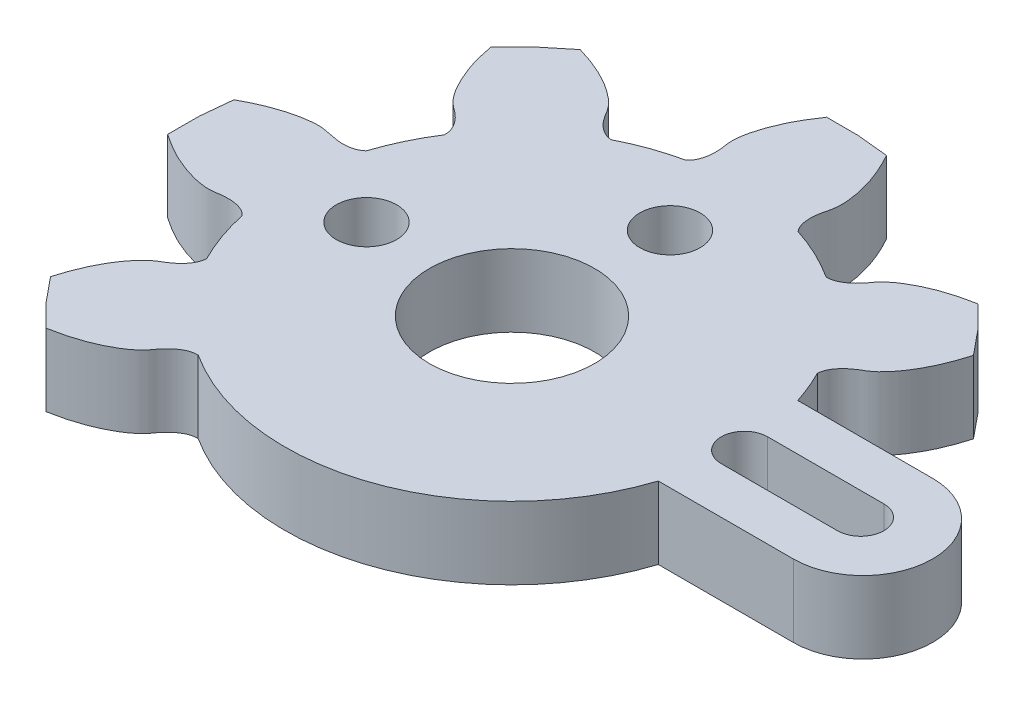
SolidWorks part; units mm, degrees
ref_plane "Front Plane" through (0, 0, 0) normal (0, 0, 1) x (1, 0, 0)
ref_plane "Top Plane" through (0, 0, 0) normal (0, 1, 0) x (1, 0, 0)
ref_plane "Right Plane" through (0, 0, 0) normal (1, 0, 0) x (0, 0, -1)
sketch "Sketch1" plane through (0, 0, 0) normal (0, 1, 0) x (1, 0, 0)
  line L0 (3.621, -0.0001) -> (-10.658, -0.0001) construction
  line L1 (-3.508, 0.8974) -> (3.508, -0.8973) construction
  line L2 (0.8972, 3.508) -> (-0.8972, -3.5081) construction
  line L3 (-6.7582, 1.6977) -> (-6.7583, -0.9523) construction
  line L4 (-8.0831, 0.3728) -> (-5.4334, 0.3728) construction
  line L5 (-1.1163, 6.723) -> (1.5333, 6.723) construction
  line L6 (0.2086, 8.0479) -> (0.2084, 5.3979) construction
  line L8 (10.2001, 1.02) -> (15.3001, 1.02)
  line L10 (10.2001, -1.02) -> (15.3001, -1.02)
  line L11 (15.402, 3.06) -> (15.402, -3.06) construction
  line L12 (15.402, -3.06) -> (9.479, -3.06)
  line L13 (15.402, 3.06) -> (9.4793, 3.06)
  line L809 (11.6208, 8.6285) -> (10.7416, 9.701)
  line L810 (10.7416, 9.701) -> (9.7639, 10.6846)
  line L853 (2.1159, 14.3182) -> (0.7358, 14.455)
  line L854 (0.7358, 14.455) -> (-0.651, 14.4591)
  line L875 (-2.1014, 9.7366) -> (-2.1021, 9.7364)
  line L897 (-8.6285, 11.6207) -> (-9.701, 10.7414)
  line L898 (-9.701, 10.7414) -> (-10.6845, 9.7637)
  line L919 (-8.3708, 5.3989) -> (-8.3715, 5.3976)
  line L920 (-9.4728, 3.0795) -> (-9.4729, 3.079)
  line L941 (-14.3183, 2.1157) -> (-14.4551, 0.7356)
  line L942 (-14.4551, 0.7356) -> (-14.459, -0.6512)
  line L963 (-9.7366, -2.1014) -> (-9.7363, -2.1023)
  line L964 (-8.8759, -4.5205) -> (-8.8757, -4.5211)
  line L985 (-11.6206, -8.6286) -> (-10.7416, -9.7011)
  line L986 (-10.7416, -9.7011) -> (-9.7637, -10.6846)
  circle A0 centre (0, 0) radius 3.621
  circle A1 centre (-6.7583, 0.3727) radius 1.3249
  circle A2 centre (0.2085, 6.723) radius 1.3248
  arc A3 (8.8758, 4.5212) -> (9.4793, 3.06) centre (0, 0) cw
  arc A4 (15.3001, -1.02) -> (15.3001, 1.02) centre (15.3001, -0.0001) ccw
  arc A5 (10.2001, 1.02) -> (10.2001, -1.02) centre (10.2001, -0.0001) ccw
  arc A6 (3.0705, 9.4841) -> (5.4131, 8.371) centre (0, 0) cw
  arc A7 (15.402, -3.06) -> (15.402, 3.06) centre (15.402, 0) ccw
  arc A8 (-8.3715, 5.3976) -> (-9.4728, 3.0795) centre (0, 0) ccw
  arc A9 (-2.1021, 9.7364) -> (-4.5212, 8.8755) centre (0, 0) ccw
  arc A11 (-9.7363, -2.1023) -> (-8.8759, -4.5205) centre (0, 0) ccw
  arc A12 (-5.3979, -8.3713) -> (9.479, -3.06) centre (0, 0) ccw
  spline S0 degree 3 poles (8.8758, 4.5212) (8.88, 4.5545) (8.8843, 4.5879) (8.8886, 4.6212) (8.8894, 4.6279) (8.8912, 4.6414) (8.8949, 4.6615) (8.8986, 4.6746) (8.9005, 4.6811) (8.9056, 4.6988) (8.9106, 4.7166) (8.9157, 4.7343) (8.9173, 4.7399) (8.9205, 4.7511) (8.9261, 4.7677) (8.9305, 4.7784) (8.9327, 4.7838) (8.939, 4.7991) (8.9452, 4.8145) (8.9515, 4.8298) (8.9535, 4.8347) (8.9575, 4.8445) (8.9641, 4.8591) (8.969, 4.8685) (8.9714, 4.8732) (8.9785, 4.8869) (8.9855, 4.9005) (8.9926, 4.9142) (8.9949, 4.9186) (8.9995, 4.9275) (9.0068, 4.9406) (9.012, 4.9492) (9.0147, 4.9534) (9.0223, 4.9659) (9.03, 4.9785) (9.0377, 4.991) (9.0414, 4.997) (9.0488, 5.0091) (9.0615, 5.0262) (9.07, 5.0376) (9.0742, 5.0433) (9.0909, 5.0656) (9.1077, 5.088) (9.1244, 5.1103) (9.1298, 5.1176) (9.1407, 5.1322) (9.1582, 5.1533) (9.1705, 5.1668) (9.1767, 5.1735) (9.1948, 5.1932) (9.2129, 5.213) (9.2311, 5.2327) (9.237, 5.2392) (9.249, 5.2522) (9.2677, 5.271) (9.2807, 5.2829) (9.2872, 5.2889) (9.3065, 5.3066) (9.3257, 5.3243) (9.345, 5.342) (9.3545, 5.3507) (9.3735, 5.3682) (9.4047, 5.3914) (9.4254, 5.4068) (9.4357, 5.4145) (9.4769, 5.4451) (9.5181, 5.4758) (9.5593, 5.5064) (9.5729, 5.5166) (9.6003, 5.5369) (9.643, 5.5651) (9.6725, 5.5822) (9.6872, 5.5907) (9.7313, 5.6163) (9.7755, 5.6419) (9.8196, 5.6675) (9.8343, 5.676) (9.8638, 5.6931) (9.9064, 5.7216) (9.9336, 5.7422) (9.9472, 5.7525) (9.9881, 5.7835) (10.029, 5.8146) (10.07, 5.8457) (10.0838, 5.8561) (10.1114, 5.8771) (10.1504, 5.9118) (10.1746, 5.9367) (10.1867, 5.9491) (10.2236, 5.987) (10.2605, 6.0248) (10.2974, 6.0627) (10.3098, 6.0755) (10.3347, 6.1011) (10.3704, 6.1411) (10.3929, 6.1688) (10.4042, 6.1826) (10.4385, 6.2246) (10.4727, 6.2667) (10.507, 6.3087) (10.5186, 6.3229) (10.5417, 6.3512) (10.5749, 6.3951) (10.5959, 6.4251) (10.6064, 6.4401) (10.6384, 6.4856) (10.6703, 6.5311) (10.7023, 6.5767) (10.7131, 6.592) (10.7346, 6.6227) (10.7655, 6.6699) (10.785, 6.7019) (10.7948, 6.7179) (10.8245, 6.7665) (10.8541, 6.8152) (10.8838, 6.8638) (10.8938, 6.8802) (10.9139, 6.913) (10.9424, 6.9631) (10.9606, 6.997) (10.9696, 7.0139) (10.9972, 7.0653) (11.0247, 7.1168) (11.0523, 7.1682) (11.0615, 7.1855) (11.0801, 7.2202) (11.1065, 7.273) (11.1232, 7.3087) (11.1315, 7.3265) (11.1568, 7.3806) (11.1822, 7.4347) (11.2075, 7.4888) (11.216, 7.507) (11.2331, 7.5435) (11.2573, 7.5989) (11.2725, 7.6361) (11.2802, 7.6547) (11.3033, 7.7113) (11.3264, 7.7678) (11.3496, 7.8244) (11.3573, 7.8434) (11.3729, 7.8815) (11.3949, 7.9392) (11.4086, 7.978) (11.4155, 7.9974) (11.4363, 8.0563) (11.4572, 8.1151) (11.478, 8.174) (11.485, 8.1938) (11.4991, 8.2335) (11.5187, 8.2935) (11.531, 8.3337) (11.5371, 8.3538) (11.565, 8.4454) (11.5929, 8.537) (11.6208, 8.6285) knots 0 0 0 0 0.019853 0.019853 0.019853 0.023862 0.02787 0.031878 0.031878 0.031878 0.042761 0.042761 0.042761 0.046198 0.049635 0.053072 0.053072 0.053072 0.06284 0.06284 0.06284 0.065977 0.069113 0.07225 0.07225 0.07225 0.081322 0.081322 0.081322 0.084276 0.08723 0.090185 0.090185 0.090185 0.098852 0.098852 0.098852 0.103039 0.107226 0.111413 0.111413 0.111413 0.127893 0.127893 0.127893 0.133271 0.13865 0.144028 0.144028 0.144028 0.15986 0.15986 0.15986 0.16507 0.170279 0.175489 0.175489 0.175489 0.190945 0.190945 0.190945 0.198563 0.206181 0.213799 0.213799 0.213799 0.244106 0.244106 0.244106 0.254159 0.264213 0.274266 0.274266 0.274266 0.304379 0.304379 0.304379 0.314436 0.324492 0.334549 0.334549 0.334549 0.364891 0.364891 0.364891 0.375124 0.385357 0.39559 0.39559 0.39559 0.426817 0.426817 0.426817 0.437349 0.447881 0.458413 0.458413 0.458413 0.490441 0.490441 0.490441 0.501247 0.512053 0.522859 0.522859 0.522859 0.555709 0.555709 0.555709 0.566786 0.577862 0.588938 0.588938 0.588938 0.622581 0.622581 0.622581 0.633925 0.645269 0.656613 0.656613 0.656613 0.69106 0.69106 0.69106 0.702675 0.71429 0.725906 0.725906 0.725906 0.761174 0.761174 0.761174 0.77306 0.784946 0.796832 0.796832 0.796832 0.8329 0.8329 0.8329 0.845051 0.857203 0.869354 0.869354 0.869354 0.906216 0.906216 0.906216 0.918637 0.931058 0.943478 0.943478 0.943478 1 1 1 1
  spline S1 degree 3 poles (9.7639, 10.6846) (9.6699, 10.6662) (9.576, 10.6478) (9.4821, 10.6294) (9.4614, 10.6253) (9.4202, 10.6172) (9.3585, 10.6037) (9.3176, 10.5938) (9.2972, 10.5888) (9.2365, 10.574) (9.1759, 10.5592) (9.1152, 10.5444) (9.0952, 10.5396) (9.0552, 10.5298) (8.9956, 10.5138) (8.9561, 10.5022) (8.9363, 10.4964) (8.8777, 10.4791) (8.8192, 10.4619) (8.7606, 10.4446) (8.7412, 10.4389) (8.7026, 10.4276) (8.6451, 10.4091) (8.6071, 10.3958) (8.5881, 10.3892) (8.5317, 10.3695) (8.4754, 10.3498) (8.419, 10.3301) (8.4004, 10.3236) (8.3633, 10.3106) (8.3081, 10.2897) (8.2717, 10.2748) (8.2535, 10.2673) (8.1995, 10.2451) (8.1455, 10.223) (8.0915, 10.2008) (8.0738, 10.1935) (8.0382, 10.1789) (7.9855, 10.1555) (7.9508, 10.1389) (7.9335, 10.1306) (7.8821, 10.106) (7.8307, 10.0814) (7.7793, 10.0568) (7.7624, 10.0487) (7.7286, 10.0325) (7.6786, 10.0066) (7.6458, 9.9883) (7.6295, 9.9791) (7.5809, 9.952) (7.5324, 9.9248) (7.4839, 9.8977) (7.4679, 9.8887) (7.4359, 9.8709) (7.3889, 9.8424) (7.3584, 9.8223) (7.3431, 9.8122) (7.2978, 9.7824) (7.2524, 9.7525) (7.2071, 9.7227) (7.1922, 9.7129) (7.1624, 9.6933) (7.1189, 9.6619) (7.091, 9.6397) (7.077, 9.6286) (7.0356, 9.5957) (6.9941, 9.5629) (6.9527, 9.53) (6.9391, 9.5192) (6.912, 9.4976) (6.8734, 9.4623) (6.8497, 9.437) (6.8379, 9.4243) (6.8028, 9.3868) (6.7677, 9.3492) (6.7326, 9.3117) (6.721, 9.2992) (6.6977, 9.2743) (6.6651, 9.2348) (6.6451, 9.2072) (6.6351, 9.1934) (6.6052, 9.1521) (6.5753, 9.1107) (6.5454, 9.0694) (6.5354, 9.0556) (6.5155, 9.028) (6.483, 8.9883) (6.46, 8.9632) (6.4485, 8.9507) (6.4139, 8.9128) (6.3792, 8.875) (6.3445, 8.8371) (6.3358, 8.8276) (6.3184, 8.8086) (6.2921, 8.78) (6.2728, 8.7628) (6.2632, 8.7543) (6.2436, 8.7369) (6.2241, 8.7195) (6.2045, 8.7021) (6.1979, 8.6963) (6.1847, 8.6846) (6.1641, 8.6678) (6.15, 8.6573) (6.1429, 8.652) (6.1215, 8.636) (6.1, 8.6199) (6.0785, 8.6039) (6.0713, 8.5985) (6.0567, 8.5876) (6.0339, 8.5724) (6.0183, 8.563) (6.0104, 8.5583) (5.9865, 8.5439) (5.9626, 8.5296) (5.9386, 8.5152) (5.9326, 8.5116) (5.9204, 8.5043) (5.9021, 8.4933) (5.8893, 8.4872) (5.8829, 8.4841) (5.8697, 8.4778) (5.8565, 8.4714) (5.8433, 8.4651) (5.8388, 8.4629) (5.8297, 8.4586) (5.8159, 8.4526) (5.8066, 8.4489) (5.8019, 8.4471) (5.7876, 8.4414) (5.7733, 8.4358) (5.7589, 8.4301) (5.754, 8.4282) (5.7441, 8.4243) (5.729, 8.4192) (5.7188, 8.4162) (5.7137, 8.4147) (5.6978, 8.41) (5.682, 8.4054) (5.6661, 8.4007) (5.6605, 8.3991) (5.6494, 8.3958) (5.6323, 8.392) (5.6209, 8.3899) (5.6151, 8.3889) (5.597, 8.3857) (5.5788, 8.3824) (5.5607, 8.3792) (5.554, 8.378) (5.5406, 8.3756) (5.5202, 8.374) (5.5066, 8.3736) (5.4998, 8.3734) (5.4709, 8.3726) (5.442, 8.3718) (5.4131, 8.371) knots 0 0 0 0 0.056516 0.056516 0.056516 0.068936 0.081355 0.093775 0.093775 0.093775 0.130635 0.130635 0.130635 0.142786 0.154938 0.167089 0.167089 0.167089 0.203158 0.203158 0.203158 0.215042 0.226926 0.23881 0.23881 0.23881 0.274066 0.274066 0.274066 0.285681 0.297296 0.308911 0.308911 0.308911 0.343368 0.343368 0.343368 0.354713 0.366059 0.377404 0.377404 0.377404 0.411046 0.411046 0.411046 0.42212 0.433194 0.444268 0.444268 0.444268 0.477104 0.477104 0.477104 0.487909 0.498714 0.509519 0.509519 0.509519 0.541555 0.541555 0.541555 0.552089 0.562624 0.573158 0.573158 0.573158 0.604391 0.604391 0.604391 0.614627 0.624863 0.635098 0.635098 0.635098 0.665448 0.665448 0.665448 0.675506 0.685563 0.695621 0.695621 0.695621 0.725735 0.725735 0.725735 0.735788 0.745841 0.755895 0.755895 0.755895 0.786201 0.786201 0.786201 0.793819 0.801436 0.809054 0.809054 0.809054 0.824508 0.824508 0.824508 0.829716 0.834924 0.840132 0.840132 0.840132 0.855952 0.855952 0.855952 0.861329 0.866706 0.872083 0.872083 0.872083 0.888565 0.888565 0.888565 0.892751 0.896937 0.901123 0.901123 0.901123 0.909781 0.909781 0.909781 0.912738 0.915695 0.918652 0.918652 0.918652 0.927749 0.927749 0.927749 0.930888 0.934027 0.937165 0.937165 0.937165 0.946918 0.946918 0.946918 0.950353 0.953788 0.957222 0.957222 0.957222 0.968108 0.968108 0.968108 0.972118 0.976128 0.980138 0.980138 0.980138 0.997214 0.997214 0.997214 0.997214
  spline S2 degree 3 poles (3.0705, 9.4841) (3.0528, 9.507) (3.0352, 9.5299) (3.0176, 9.5528) (3.0134, 9.5582) (3.0051, 9.569) (2.9935, 9.5858) (2.9869, 9.5977) (2.9836, 9.6036) (2.9747, 9.6197) (2.9657, 9.6358) (2.9568, 9.6519) (2.9539, 9.657) (2.9483, 9.6671) (2.9405, 9.6828) (2.936, 9.6935) (2.9338, 9.6989) (2.9274, 9.7141) (2.921, 9.7294) (2.9146, 9.7446) (2.9125, 9.7495) (2.9084, 9.7593) (2.9028, 9.7743) (2.8995, 9.7844) (2.8979, 9.7894) (2.8932, 9.8041) (2.8886, 9.8188) (2.8839, 9.8335) (2.8824, 9.8382) (2.8793, 9.8478) (2.8752, 9.8622) (2.8729, 9.872) (2.8717, 9.8768) (2.8683, 9.8911) (2.8649, 9.9054) (2.8615, 9.9197) (2.8598, 9.9265) (2.8565, 9.9403) (2.8534, 9.9615) (2.8513, 9.9755) (2.8503, 9.9825) (2.8463, 10.0102) (2.8423, 10.0378) (2.8383, 10.0655) (2.837, 10.0745) (2.8343, 10.0925) (2.8317, 10.1198) (2.831, 10.138) (2.8306, 10.1471) (2.8295, 10.1738) (2.8284, 10.2006) (2.8273, 10.2273) (2.8269, 10.2361) (2.8262, 10.2538) (2.8262, 10.2802) (2.8269, 10.2979) (2.8273, 10.3067) (2.8284, 10.3328) (2.8294, 10.359) (2.8305, 10.3851) (2.8311, 10.398) (2.8321, 10.4238) (2.8377, 10.4622) (2.8415, 10.4878) (2.8434, 10.5005) (2.8508, 10.5513) (2.8583, 10.6022) (2.8658, 10.6529) (2.8682, 10.6698) (2.8732, 10.7035) (2.8835, 10.7537) (2.8922, 10.7866) (2.8966, 10.8031) (2.9097, 10.8524) (2.9229, 10.9017) (2.936, 10.951) (2.9404, 10.9675) (2.9491, 11.0004) (2.9592, 11.0507) (2.9638, 11.0844) (2.9661, 11.1013) (2.9731, 11.1522) (2.98, 11.2032) (2.987, 11.2541) (2.9893, 11.2712) (2.994, 11.3056) (2.9971, 11.3578) (2.9966, 11.3924) (2.9964, 11.4098) (2.9957, 11.4626) (2.9951, 11.5155) (2.9944, 11.5684) (2.9941, 11.5862) (2.9937, 11.6219) (2.9905, 11.6754) (2.9869, 11.7109) (2.9851, 11.7286) (2.9796, 11.7826) (2.9741, 11.8365) (2.9686, 11.8905) (2.9667, 11.9087) (2.963, 11.9451) (2.9554, 11.9996) (2.9491, 12.0356) (2.946, 12.0536) (2.9364, 12.1084) (2.9268, 12.1632) (2.9172, 12.218) (2.9139, 12.2365) (2.9074, 12.2734) (2.8959, 12.3285) (2.8871, 12.365) (2.8827, 12.3833) (2.8693, 12.4387) (2.856, 12.4941) (2.8426, 12.5495) (2.8381, 12.5681) (2.8291, 12.6055) (2.8139, 12.6612) (2.8027, 12.6979) (2.7972, 12.7163) (2.7802, 12.7722) (2.7633, 12.828) (2.7464, 12.8839) (2.7406, 12.9027) (2.7292, 12.9404) (2.7105, 12.9964) (2.6971, 13.0334) (2.6905, 13.0519) (2.6701, 13.108) (2.6498, 13.1642) (2.6295, 13.2203) (2.6226, 13.2392) (2.6089, 13.2771) (2.5869, 13.3334) (2.5713, 13.3705) (2.5635, 13.389) (2.5399, 13.4453) (2.5162, 13.5017) (2.4926, 13.558) (2.4846, 13.5769) (2.4687, 13.6149) (2.4434, 13.6712) (2.4257, 13.7084) (2.4169, 13.727) (2.39, 13.7833) (2.3632, 13.8397) (2.3363, 13.896) (2.3273, 13.915) (2.3092, 13.953) (2.2807, 14.0093) (2.2609, 14.0464) (2.251, 14.065) (2.206, 14.1494) (2.1609, 14.2338) (2.1159, 14.3182) knots 0.00277 0.00277 0.00277 0.00277 0.019842 0.019842 0.019842 0.023849 0.027855 0.031862 0.031862 0.031862 0.042739 0.042739 0.042739 0.046172 0.049606 0.05304 0.05304 0.05304 0.062797 0.062797 0.062797 0.065935 0.069073 0.072212 0.072212 0.072212 0.081303 0.081303 0.081303 0.08426 0.087217 0.090174 0.090174 0.090174 0.098836 0.098836 0.098836 0.103026 0.107215 0.111405 0.111405 0.111405 0.127903 0.127903 0.127903 0.133281 0.138658 0.144036 0.144036 0.144036 0.159845 0.159845 0.159845 0.165051 0.170257 0.175463 0.175463 0.175463 0.190918 0.190918 0.190918 0.198537 0.206157 0.213776 0.213776 0.213776 0.244096 0.244096 0.244096 0.254153 0.26421 0.274268 0.274268 0.274268 0.304392 0.304392 0.304392 0.314451 0.32451 0.334568 0.334568 0.334568 0.364914 0.364914 0.364914 0.375147 0.385379 0.395612 0.395612 0.395612 0.426832 0.426832 0.426832 0.437363 0.447895 0.458426 0.458426 0.458426 0.490458 0.490458 0.490458 0.501264 0.512069 0.522874 0.522874 0.522874 0.555716 0.555716 0.555716 0.566793 0.577869 0.588946 0.588946 0.588946 0.622598 0.622598 0.622598 0.633945 0.645293 0.65664 0.65664 0.65664 0.691102 0.691102 0.691102 0.702718 0.714335 0.725952 0.725952 0.725952 0.761215 0.761215 0.761215 0.773099 0.784983 0.796867 0.796867 0.796867 0.832931 0.832931 0.832931 0.845081 0.857231 0.869382 0.869382 0.869382 0.90624 0.90624 0.90624 0.918658 0.931076 0.943495 0.943495 0.943495 1 1 1 1
  spline S3 degree 3 poles (-0.651, 14.4591) (-0.7044, 14.3797) (-0.7578, 14.3003) (-0.8112, 14.2209) (-0.823, 14.2034) (-0.8465, 14.1685) (-0.8805, 14.1153) (-0.9024, 14.0794) (-0.9133, 14.0614) (-0.9458, 14.0081) (-0.9782, 13.9547) (-1.0107, 13.9014) (-1.0214, 13.8838) (-1.0428, 13.8486) (-1.0736, 13.7951) (-1.0933, 13.759) (-1.1032, 13.7409) (-1.1324, 13.6873) (-1.1617, 13.6336) (-1.1909, 13.58) (-1.2005, 13.5623) (-1.2198, 13.527) (-1.2474, 13.4733) (-1.2649, 13.437) (-1.2736, 13.4189) (-1.2995, 13.3651) (-1.3255, 13.3113) (-1.3514, 13.2575) (-1.3599, 13.2398) (-1.377, 13.2044) (-1.4012, 13.1505) (-1.4164, 13.1142) (-1.424, 13.0961) (-1.4465, 13.0422) (-1.469, 12.9884) (-1.4915, 12.9345) (-1.4989, 12.9168) (-1.5137, 12.8813) (-1.5345, 12.8275) (-1.5473, 12.7913) (-1.5537, 12.7731) (-1.5726, 12.7194) (-1.5916, 12.6657) (-1.6105, 12.6119) (-1.6168, 12.5943) (-1.6292, 12.5589) (-1.6463, 12.5052) (-1.6565, 12.4691) (-1.6616, 12.451) (-1.6767, 12.3975) (-1.6918, 12.344) (-1.7069, 12.2905) (-1.7119, 12.2728) (-1.7218, 12.2376) (-1.7349, 12.1842) (-1.7423, 12.1484) (-1.7459, 12.1304) (-1.7569, 12.0773) (-1.7678, 12.0241) (-1.7787, 11.971) (-1.7823, 11.9535) (-1.7895, 11.9186) (-1.7981, 11.8657) (-1.8022, 11.8302) (-1.8042, 11.8125) (-1.8103, 11.76) (-1.8164, 11.7075) (-1.8224, 11.655) (-1.8244, 11.6378) (-1.8284, 11.6034) (-1.8307, 11.5511) (-1.8295, 11.5165) (-1.8289, 11.4992) (-1.8271, 11.4478) (-1.8254, 11.3964) (-1.8236, 11.345) (-1.823, 11.328) (-1.8218, 11.294) (-1.817, 11.2429) (-1.8116, 11.2092) (-1.8089, 11.1924) (-1.8009, 11.1421) (-1.7928, 11.0917) (-1.7848, 11.0414) (-1.7821, 11.0246) (-1.7768, 10.9909) (-1.7716, 10.9399) (-1.7701, 10.9059) (-1.7693, 10.8889) (-1.767, 10.8376) (-1.7648, 10.7863) (-1.7625, 10.735) (-1.7619, 10.7221) (-1.7608, 10.6963) (-1.7591, 10.6575) (-1.7606, 10.6318) (-1.7614, 10.6189) (-1.7629, 10.5928) (-1.7645, 10.5666) (-1.766, 10.5405) (-1.7665, 10.5317) (-1.7676, 10.5141) (-1.7703, 10.4878) (-1.7729, 10.4703) (-1.7741, 10.4616) (-1.778, 10.4351) (-1.7818, 10.4085) (-1.7857, 10.382) (-1.787, 10.373) (-1.7896, 10.355) (-1.795, 10.3281) (-1.7994, 10.3104) (-1.8016, 10.3016) (-1.8083, 10.2745) (-1.8151, 10.2474) (-1.8218, 10.2203) (-1.8235, 10.2134) (-1.827, 10.1997) (-1.8322, 10.179) (-1.8369, 10.1656) (-1.8392, 10.1589) (-1.8441, 10.1451) (-1.849, 10.1312) (-1.8538, 10.1174) (-1.8555, 10.1127) (-1.8588, 10.1032) (-1.8644, 10.0892) (-1.8684, 10.0801) (-1.8704, 10.0755) (-1.8765, 10.0614) (-1.8827, 10.0472) (-1.8888, 10.0331) (-1.8909, 10.0282) (-1.8952, 10.0185) (-1.9023, 10.0042) (-1.9074, 9.9948) (-1.9099, 9.9902) (-1.9179, 9.9757) (-1.9258, 9.9611) (-1.9337, 9.9466) (-1.9365, 9.9415) (-1.9421, 9.9313) (-1.9515, 9.9165) (-1.9581, 9.907) (-1.9614, 9.9022) (-1.9719, 9.8871) (-1.9825, 9.8719) (-1.993, 9.8568) (-1.9968, 9.8513) (-2.0046, 9.8401) (-2.0179, 9.8245) (-2.0272, 9.8147) (-2.0319, 9.8098) (-2.0551, 9.7854) (-2.0782, 9.761) (-2.1014, 9.7366) knots 0 0 0 0 0.056512 0.056512 0.056512 0.068933 0.081354 0.093775 0.093775 0.093775 0.130646 0.130646 0.130646 0.142799 0.154952 0.167105 0.167105 0.167105 0.203173 0.203173 0.203173 0.215055 0.226938 0.238821 0.238821 0.238821 0.274073 0.274073 0.274073 0.285688 0.297302 0.308917 0.308917 0.308917 0.343378 0.343378 0.343378 0.354724 0.36607 0.377416 0.377416 0.377416 0.411059 0.411059 0.411059 0.422134 0.433209 0.444285 0.444285 0.444285 0.477128 0.477128 0.477128 0.487935 0.498742 0.509549 0.509549 0.509549 0.541589 0.541589 0.541589 0.55212 0.562651 0.573182 0.573182 0.573182 0.604387 0.604387 0.604387 0.614619 0.624851 0.635083 0.635083 0.635083 0.665442 0.665442 0.665442 0.6755 0.685558 0.695616 0.695616 0.695616 0.725722 0.725722 0.725722 0.735777 0.745831 0.755886 0.755886 0.755886 0.786207 0.786207 0.786207 0.793826 0.801445 0.809064 0.809064 0.809064 0.824512 0.824512 0.824512 0.829719 0.834926 0.840133 0.840133 0.840133 0.855955 0.855955 0.855955 0.861333 0.866712 0.87209 0.87209 0.87209 0.888581 0.888581 0.888581 0.892768 0.896956 0.901143 0.901143 0.901143 0.909802 0.909802 0.909802 0.912758 0.915715 0.918672 0.918672 0.918672 0.927764 0.927764 0.927764 0.930904 0.934044 0.937184 0.937184 0.937184 0.946952 0.946952 0.946952 0.950388 0.953823 0.957258 0.957258 0.957258 0.968132 0.968132 0.968132 0.972138 0.976144 0.980151 0.980151 0.980151 1 1 1 1
  spline S4 degree 3 poles (-4.5212, 8.8755) (-4.5545, 8.8798) (-4.5878, 8.8841) (-4.6211, 8.8885) (-4.6279, 8.8893) (-4.6413, 8.8911) (-4.6615, 8.8948) (-4.6745, 8.8985) (-4.681, 8.9004) (-4.6988, 8.9054) (-4.7165, 8.9105) (-4.7342, 8.9155) (-4.7398, 8.9171) (-4.751, 8.9203) (-4.7676, 8.9259) (-4.7784, 8.9303) (-4.7838, 8.9325) (-4.7991, 8.9388) (-4.8144, 8.945) (-4.8297, 8.9513) (-4.8346, 8.9533) (-4.8445, 8.9573) (-4.859, 8.9639) (-4.8684, 8.9688) (-4.8731, 8.9712) (-4.8868, 8.9783) (-4.9005, 8.9854) (-4.9141, 8.9925) (-4.9186, 8.9947) (-4.9275, 8.9993) (-4.9406, 9.0067) (-4.9492, 9.0119) (-4.9534, 9.0145) (-4.9659, 9.0222) (-4.9785, 9.0298) (-4.991, 9.0375) (-4.997, 9.0412) (-5.0091, 9.0486) (-5.0263, 9.0613) (-5.0376, 9.0698) (-5.0433, 9.0741) (-5.0657, 9.0908) (-5.088, 9.1076) (-5.1104, 9.1243) (-5.1177, 9.1298) (-5.1323, 9.1407) (-5.1534, 9.1581) (-5.1668, 9.1705) (-5.1735, 9.1766) (-5.1932, 9.1947) (-5.213, 9.2129) (-5.2327, 9.231) (-5.2392, 9.2369) (-5.2521, 9.2489) (-5.2709, 9.2676) (-5.2829, 9.2805) (-5.2888, 9.287) (-5.3065, 9.3063) (-5.3243, 9.3255) (-5.342, 9.3448) (-5.3507, 9.3543) (-5.3682, 9.3733) (-5.3914, 9.4044) (-5.4068, 9.4251) (-5.4145, 9.4355) (-5.4451, 9.4767) (-5.4758, 9.5179) (-5.5064, 9.5591) (-5.5166, 9.5728) (-5.5369, 9.6001) (-5.5651, 9.6429) (-5.5822, 9.6724) (-5.5907, 9.6871) (-5.6163, 9.7312) (-5.6418, 9.7754) (-5.6674, 9.8195) (-5.6759, 9.8342) (-5.693, 9.8637) (-5.7215, 9.9064) (-5.7421, 9.9335) (-5.7524, 9.9471) (-5.7835, 9.988) (-5.8146, 10.029) (-5.8457, 10.0699) (-5.8562, 10.0837) (-5.8771, 10.1113) (-5.9119, 10.1504) (-5.9367, 10.1746) (-5.9491, 10.1867) (-5.987, 10.2236) (-6.0248, 10.2604) (-6.0627, 10.2973) (-6.0754, 10.3098) (-6.101, 10.3347) (-6.1411, 10.3703) (-6.1687, 10.3928) (-6.1825, 10.4041) (-6.2246, 10.4384) (-6.2666, 10.4726) (-6.3087, 10.5069) (-6.3229, 10.5185) (-6.3512, 10.5416) (-6.3951, 10.5747) (-6.4251, 10.5958) (-6.44, 10.6063) (-6.4856, 10.6382) (-6.5311, 10.6702) (-6.5766, 10.7021) (-6.592, 10.7129) (-6.6227, 10.7345) (-6.6699, 10.7653) (-6.7019, 10.7848) (-6.7179, 10.7946) (-6.7665, 10.8243) (-6.8152, 10.8541) (-6.8638, 10.8838) (-6.8802, 10.8938) (-6.913, 10.9138) (-6.9631, 10.9424) (-6.997, 10.9605) (-7.0139, 10.9696) (-7.0654, 10.9971) (-7.1169, 11.0246) (-7.1683, 11.0521) (-7.1857, 11.0614) (-7.2204, 11.0799) (-7.2732, 11.1063) (-7.3088, 11.123) (-7.3266, 11.1314) (-7.3807, 11.1567) (-7.4348, 11.1821) (-7.4888, 11.2074) (-7.5071, 11.216) (-7.5435, 11.2331) (-7.5989, 11.2573) (-7.6361, 11.2725) (-7.6547, 11.2801) (-7.7113, 11.3032) (-7.7678, 11.3263) (-7.8243, 11.3494) (-7.8434, 11.3572) (-7.8815, 11.3727) (-7.9392, 11.3947) (-7.978, 11.4085) (-7.9974, 11.4154) (-8.0562, 11.4362) (-8.1151, 11.4571) (-8.1739, 11.478) (-8.1937, 11.485) (-8.2334, 11.499) (-8.2934, 11.5187) (-8.3336, 11.531) (-8.3537, 11.5371) (-8.4453, 11.5649) (-8.5369, 11.5928) (-8.6285, 11.6207) knots 0 0 0 0 0.019841 0.019841 0.019841 0.023849 0.027857 0.031866 0.031866 0.031866 0.042756 0.042756 0.042756 0.046192 0.049628 0.053065 0.053065 0.053065 0.062824 0.062824 0.062824 0.065961 0.069099 0.072236 0.072236 0.072236 0.081321 0.081321 0.081321 0.084277 0.087233 0.090189 0.090189 0.090189 0.09885 0.09885 0.09885 0.10304 0.107229 0.111419 0.111419 0.111419 0.127918 0.127918 0.127918 0.133297 0.138675 0.144053 0.144053 0.144053 0.159864 0.159864 0.159864 0.165069 0.170274 0.175479 0.175479 0.175479 0.190927 0.190927 0.190927 0.198546 0.206165 0.213785 0.213785 0.213785 0.244108 0.244108 0.244108 0.254163 0.264219 0.274274 0.274274 0.274274 0.304382 0.304382 0.304382 0.314441 0.3245 0.334559 0.334559 0.334559 0.364922 0.364922 0.364922 0.375155 0.385388 0.395621 0.395621 0.395621 0.426826 0.426826 0.426826 0.437356 0.447886 0.458416 0.458416 0.458416 0.490452 0.490452 0.490452 0.501259 0.512065 0.522871 0.522871 0.522871 0.555716 0.555716 0.555716 0.566794 0.577871 0.588948 0.588948 0.588948 0.622602 0.622602 0.622602 0.633948 0.645295 0.656642 0.656642 0.656642 0.691098 0.691098 0.691098 0.702713 0.714328 0.725944 0.725944 0.725944 0.761203 0.761203 0.761203 0.773086 0.784969 0.796852 0.796852 0.796852 0.832913 0.832913 0.832913 0.845063 0.857213 0.869363 0.869363 0.869363 0.906223 0.906223 0.906223 0.918643 0.931062 0.943482 0.943482 0.943482 1 1 1 1
  spline S5 degree 3 poles (-10.6845, 9.7637) (-10.6661, 9.6698) (-10.6477, 9.5759) (-10.6293, 9.482) (-10.6253, 9.4613) (-10.6172, 9.42) (-10.6037, 9.3584) (-10.5938, 9.3175) (-10.5888, 9.2971) (-10.574, 9.2364) (-10.5593, 9.1757) (-10.5445, 9.1151) (-10.5396, 9.0951) (-10.5299, 9.0551) (-10.5139, 8.9954) (-10.5022, 8.9559) (-10.4964, 8.9362) (-10.4791, 8.8776) (-10.4619, 8.8191) (-10.4446, 8.7605) (-10.4389, 8.7412) (-10.4275, 8.7026) (-10.409, 8.6451) (-10.3958, 8.6071) (-10.3891, 8.5881) (-10.3694, 8.5317) (-10.3498, 8.4753) (-10.3301, 8.4189) (-10.3236, 8.4003) (-10.3106, 8.3632) (-10.2897, 8.308) (-10.2748, 8.2716) (-10.2673, 8.2533) (-10.2451, 8.1993) (-10.223, 8.1453) (-10.2008, 8.0913) (-10.1935, 8.0736) (-10.1789, 8.038) (-10.1555, 7.9853) (-10.1389, 7.9506) (-10.1306, 7.9333) (-10.106, 7.8819) (-10.0814, 7.8305) (-10.0568, 7.7791) (-10.0487, 7.7622) (-10.0325, 7.7284) (-10.0066, 7.6784) (-9.9883, 7.6456) (-9.9791, 7.6293) (-9.952, 7.5807) (-9.9248, 7.5322) (-9.8977, 7.4837) (-9.8887, 7.4677) (-9.8709, 7.4357) (-9.8424, 7.3887) (-9.8222, 7.3582) (-9.8122, 7.3429) (-9.7823, 7.2976) (-9.7525, 7.2522) (-9.7226, 7.2069) (-9.7128, 7.192) (-9.6932, 7.1622) (-9.6618, 7.1187) (-9.6396, 7.0908) (-9.6285, 7.0768) (-9.5957, 7.0354) (-9.5628, 6.994) (-9.5299, 6.9526) (-9.5192, 6.939) (-9.4976, 6.9119) (-9.4623, 6.8733) (-9.437, 6.8497) (-9.4243, 6.8378) (-9.3867, 6.8028) (-9.3492, 6.7677) (-9.3116, 6.7326) (-9.2991, 6.721) (-9.2742, 6.6978) (-9.2347, 6.6651) (-9.2071, 6.6451) (-9.1933, 6.6352) (-9.152, 6.6052) (-9.1108, 6.5753) (-9.0695, 6.5454) (-9.0557, 6.5354) (-9.0281, 6.5154) (-8.9884, 6.4829) (-8.9633, 6.4599) (-8.9507, 6.4484) (-8.9128, 6.4138) (-8.875, 6.3791) (-8.8371, 6.3445) (-8.8276, 6.3357) (-8.8085, 6.3183) (-8.7799, 6.2921) (-8.7628, 6.2728) (-8.7542, 6.2631) (-8.7368, 6.2435) (-8.7195, 6.224) (-8.7021, 6.2044) (-8.6962, 6.1978) (-8.6845, 6.1846) (-8.6678, 6.164) (-8.6573, 6.1499) (-8.652, 6.1429) (-8.636, 6.1214) (-8.6199, 6.0999) (-8.6039, 6.0785) (-8.5984, 6.0712) (-8.5875, 6.0566) (-8.5724, 6.0338) (-8.563, 6.0181) (-8.5583, 6.0103) (-8.5439, 5.9864) (-8.5296, 5.9624) (-8.5152, 5.9385) (-8.5116, 5.9324) (-8.5043, 5.9202) (-8.4933, 5.9019) (-8.4872, 5.8891) (-8.4841, 5.8827) (-8.4777, 5.8695) (-8.4714, 5.8563) (-8.465, 5.8431) (-8.4628, 5.8386) (-8.4585, 5.8295) (-8.4525, 5.8157) (-8.4488, 5.8064) (-8.447, 5.8018) (-8.4414, 5.7874) (-8.4357, 5.7731) (-8.4301, 5.7588) (-8.4282, 5.7538) (-8.4243, 5.7439) (-8.4192, 5.7288) (-8.4162, 5.7186) (-8.4146, 5.7135) (-8.41, 5.6976) (-8.4053, 5.6818) (-8.4006, 5.6659) (-8.399, 5.6603) (-8.3957, 5.6492) (-8.3919, 5.6321) (-8.3899, 5.6207) (-8.3889, 5.6149) (-8.3856, 5.5968) (-8.3824, 5.5786) (-8.3792, 5.5605) (-8.3781, 5.5538) (-8.3757, 5.5404) (-8.3741, 5.52) (-8.3737, 5.5065) (-8.3735, 5.4997) (-8.3726, 5.4661) (-8.3717, 5.4325) (-8.3708, 5.3989) knots 0 0 0 0 0.056501 0.056501 0.056501 0.068921 0.08134 0.09376 0.09376 0.09376 0.130629 0.130629 0.130629 0.14278 0.154931 0.167082 0.167082 0.167082 0.203139 0.203139 0.203139 0.215022 0.226906 0.238789 0.238789 0.238789 0.274053 0.274053 0.274053 0.285671 0.297289 0.308907 0.308907 0.308907 0.343375 0.343375 0.343375 0.354723 0.36607 0.377417 0.377417 0.377417 0.411061 0.411061 0.411061 0.422135 0.43321 0.444285 0.444285 0.444285 0.477122 0.477122 0.477122 0.487929 0.498735 0.509541 0.509541 0.509541 0.541584 0.541584 0.541584 0.552117 0.562651 0.573185 0.573185 0.573185 0.604406 0.604406 0.604406 0.614638 0.624871 0.635103 0.635103 0.635103 0.665448 0.665448 0.665448 0.675505 0.685562 0.695619 0.695619 0.695619 0.72573 0.72573 0.72573 0.735786 0.745842 0.755898 0.755898 0.755898 0.78622 0.78622 0.78622 0.793839 0.801458 0.809077 0.809077 0.809077 0.824526 0.824526 0.824526 0.829733 0.83494 0.840147 0.840147 0.840147 0.855968 0.855968 0.855968 0.861346 0.866725 0.872104 0.872104 0.872104 0.888595 0.888595 0.888595 0.892783 0.896972 0.90116 0.90116 0.90116 0.909823 0.909823 0.909823 0.91278 0.915738 0.918695 0.918695 0.918695 0.927789 0.927789 0.927789 0.930928 0.934066 0.937205 0.937205 0.937205 0.946961 0.946961 0.946961 0.950396 0.95383 0.957265 0.957265 0.957265 0.968148 0.968148 0.968148 0.972154 0.976161 0.980167 0.980167 0.980167 1 1 1 1
  spline S6 degree 3 poles (-9.4729, 3.079) (-9.4996, 3.0585) (-9.5262, 3.038) (-9.5528, 3.0175) (-9.5582, 3.0133) (-9.569, 3.005) (-9.5858, 2.9934) (-9.5977, 2.9868) (-9.6036, 2.9835) (-9.6197, 2.9745) (-9.6358, 2.9656) (-9.6519, 2.9566) (-9.657, 2.9538) (-9.6671, 2.9481) (-9.6828, 2.9403) (-9.6936, 2.9358) (-9.6989, 2.9336) (-9.7142, 2.9272) (-9.7294, 2.9208) (-9.7447, 2.9144) (-9.7496, 2.9124) (-9.7594, 2.9083) (-9.7743, 2.9027) (-9.7845, 2.8994) (-9.7895, 2.8978) (-9.8042, 2.8931) (-9.8188, 2.8884) (-9.8335, 2.8837) (-9.8382, 2.8822) (-9.8478, 2.8791) (-9.8622, 2.875) (-9.872, 2.8727) (-9.8768, 2.8715) (-9.8911, 2.8681) (-9.9054, 2.8647) (-9.9196, 2.8613) (-9.9265, 2.8596) (-9.9403, 2.8563) (-9.9615, 2.8532) (-9.9755, 2.8512) (-9.9825, 2.8502) (-10.0102, 2.8462) (-10.0378, 2.8422) (-10.0655, 2.8382) (-10.0745, 2.8369) (-10.0925, 2.8343) (-10.1198, 2.8317) (-10.138, 2.8309) (-10.1471, 2.8305) (-10.1739, 2.8294) (-10.2007, 2.8283) (-10.2275, 2.8272) (-10.2363, 2.8268) (-10.2539, 2.826) (-10.2804, 2.826) (-10.298, 2.8267) (-10.3068, 2.8271) (-10.3329, 2.8282) (-10.3591, 2.8293) (-10.3852, 2.8304) (-10.3981, 2.8309) (-10.4238, 2.832) (-10.4623, 2.8376) (-10.4878, 2.8414) (-10.5005, 2.8432) (-10.5513, 2.8507) (-10.6022, 2.8581) (-10.6529, 2.8656) (-10.6698, 2.868) (-10.7035, 2.873) (-10.7537, 2.8833) (-10.7866, 2.8921) (-10.8031, 2.8964) (-10.8524, 2.9096) (-10.9016, 2.9227) (-10.9509, 2.9359) (-10.9674, 2.9402) (-11.0003, 2.949) (-11.0506, 2.9591) (-11.0843, 2.9637) (-11.1012, 2.966) (-11.1521, 2.973) (-11.2031, 2.9799) (-11.254, 2.9869) (-11.2711, 2.9892) (-11.3055, 2.9939) (-11.3577, 2.997) (-11.3923, 2.9965) (-11.4096, 2.9963) (-11.4625, 2.9956) (-11.5154, 2.995) (-11.5682, 2.9943) (-11.5861, 2.994) (-11.6218, 2.9936) (-11.6753, 2.9904) (-11.7108, 2.9868) (-11.7285, 2.985) (-11.7825, 2.9795) (-11.8365, 2.9741) (-11.8905, 2.9686) (-11.9087, 2.9667) (-11.9451, 2.963) (-11.9995, 2.9554) (-12.0356, 2.9491) (-12.0536, 2.9459) (-12.1084, 2.9363) (-12.1631, 2.9267) (-12.2179, 2.9171) (-12.2364, 2.9138) (-12.2733, 2.9073) (-12.3285, 2.8958) (-12.3649, 2.887) (-12.3832, 2.8826) (-12.4385, 2.8692) (-12.4939, 2.8558) (-12.5493, 2.8424) (-12.568, 2.8379) (-12.6054, 2.8289) (-12.661, 2.8137) (-12.6978, 2.8025) (-12.7162, 2.797) (-12.7721, 2.7801) (-12.8279, 2.7631) (-12.8838, 2.7462) (-12.9026, 2.7405) (-12.9402, 2.7291) (-12.9963, 2.7105) (-13.0333, 2.6971) (-13.0517, 2.6904) (-13.1079, 2.6701) (-13.164, 2.6497) (-13.2201, 2.6294) (-13.2391, 2.6226) (-13.2769, 2.6089) (-13.3332, 2.5868) (-13.3703, 2.5713) (-13.3888, 2.5635) (-13.4452, 2.5398) (-13.5015, 2.5162) (-13.5578, 2.4925) (-13.5768, 2.4846) (-13.6148, 2.4686) (-13.6711, 2.4433) (-13.7083, 2.4256) (-13.7269, 2.4167) (-13.7832, 2.3899) (-13.8396, 2.363) (-13.8959, 2.3361) (-13.9149, 2.3271) (-13.9529, 2.309) (-14.0092, 2.2805) (-14.0464, 2.2607) (-14.0649, 2.2508) (-14.1494, 2.2058) (-14.2339, 2.1608) (-14.3183, 2.1157) knots 0 0 0 0 0.01985 0.01985 0.01985 0.023859 0.027867 0.031875 0.031875 0.031875 0.042756 0.042756 0.042756 0.046192 0.049627 0.053062 0.053062 0.053062 0.062824 0.062824 0.062824 0.065962 0.0691 0.072238 0.072238 0.072238 0.081323 0.081323 0.081323 0.084278 0.087234 0.09019 0.09019 0.09019 0.098852 0.098852 0.098852 0.103041 0.10723 0.111419 0.111419 0.111419 0.127914 0.127914 0.127914 0.133294 0.138675 0.144055 0.144055 0.144055 0.159884 0.159884 0.159884 0.16509 0.170296 0.175502 0.175502 0.175502 0.190937 0.190937 0.190937 0.198553 0.206169 0.213785 0.213785 0.213785 0.244102 0.244102 0.244102 0.254157 0.264213 0.274268 0.274268 0.274268 0.304384 0.304384 0.304384 0.314441 0.324499 0.334556 0.334556 0.334556 0.364901 0.364901 0.364901 0.375133 0.385365 0.395597 0.395597 0.395597 0.426816 0.426816 0.426816 0.437349 0.447881 0.458414 0.458414 0.458414 0.490454 0.490454 0.490454 0.501259 0.512064 0.522869 0.522869 0.522869 0.555701 0.555701 0.555701 0.566777 0.577852 0.588928 0.588928 0.588928 0.622581 0.622581 0.622581 0.633928 0.645275 0.656622 0.656622 0.656622 0.691079 0.691079 0.691079 0.702693 0.714306 0.72592 0.72592 0.72592 0.761169 0.761169 0.761169 0.773053 0.784937 0.79682 0.79682 0.79682 0.832896 0.832896 0.832896 0.845049 0.857201 0.869354 0.869354 0.869354 0.906215 0.906215 0.906215 0.918636 0.931057 0.943477 0.943477 0.943477 1 1 1 1
  spline S7 degree 3 poles (-14.459, -0.6512) (-14.3796, -0.7045) (-14.3002, -0.758) (-14.2208, -0.8114) (-14.2034, -0.8231) (-14.1685, -0.8466) (-14.1153, -0.8806) (-14.0794, -0.9025) (-14.0614, -0.9134) (-14.008, -0.9459) (-13.9547, -0.9783) (-13.9013, -1.0108) (-13.8837, -1.0215) (-13.8485, -1.0429) (-13.795, -1.0737) (-13.7589, -1.0934) (-13.7408, -1.1033) (-13.6872, -1.1325) (-13.6336, -1.1617) (-13.58, -1.1909) (-13.5623, -1.2006) (-13.527, -1.2198) (-13.4732, -1.2474) (-13.437, -1.2649) (-13.4188, -1.2737) (-13.365, -1.2996) (-13.3112, -1.3256) (-13.2574, -1.3515) (-13.2397, -1.3601) (-13.2043, -1.3772) (-13.1505, -1.4014) (-13.1142, -1.4166) (-13.096, -1.4242) (-13.0422, -1.4467) (-12.9883, -1.4691) (-12.9345, -1.4916) (-12.9168, -1.499) (-12.8813, -1.5138) (-12.8275, -1.5346) (-12.7913, -1.5474) (-12.7732, -1.5538) (-12.7194, -1.5727) (-12.6657, -1.5916) (-12.612, -1.6106) (-12.5943, -1.6168) (-12.5589, -1.6293) (-12.5052, -1.6463) (-12.4691, -1.6565) (-12.451, -1.6616) (-12.3975, -1.6767) (-12.344, -1.6919) (-12.2904, -1.707) (-12.2728, -1.7119) (-12.2376, -1.7219) (-12.1842, -1.735) (-12.1484, -1.7424) (-12.1304, -1.7461) (-12.0773, -1.757) (-12.0241, -1.768) (-11.971, -1.7789) (-11.9535, -1.7825) (-11.9186, -1.7897) (-11.8656, -1.7983) (-11.8302, -1.8024) (-11.8125, -1.8044) (-11.76, -1.8105) (-11.7074, -1.8165) (-11.6549, -1.8226) (-11.6377, -1.8246) (-11.6033, -1.8285) (-11.5511, -1.8308) (-11.5164, -1.8296) (-11.4991, -1.829) (-11.4477, -1.8272) (-11.3964, -1.8255) (-11.345, -1.8237) (-11.328, -1.8231) (-11.2939, -1.8219) (-11.2429, -1.817) (-11.2092, -1.8117) (-11.1924, -1.809) (-11.142, -1.801) (-11.0917, -1.7929) (-11.0413, -1.7849) (-11.0245, -1.7822) (-10.9909, -1.7769) (-10.9399, -1.7717) (-10.9058, -1.7702) (-10.8888, -1.7695) (-10.8375, -1.7672) (-10.7863, -1.7649) (-10.735, -1.7626) (-10.7221, -1.7621) (-10.6963, -1.7609) (-10.6575, -1.7593) (-10.6318, -1.7608) (-10.6189, -1.7616) (-10.5928, -1.7631) (-10.5667, -1.7647) (-10.5406, -1.7662) (-10.5318, -1.7667) (-10.5142, -1.7678) (-10.4878, -1.7705) (-10.4704, -1.773) (-10.4616, -1.7743) (-10.4351, -1.7781) (-10.4085, -1.782) (-10.382, -1.7858) (-10.373, -1.7871) (-10.3549, -1.7897) (-10.328, -1.7951) (-10.3104, -1.7995) (-10.3015, -1.8017) (-10.2744, -1.8085) (-10.2474, -1.8153) (-10.2203, -1.8221) (-10.2134, -1.8238) (-10.1996, -1.8272) (-10.179, -1.8325) (-10.1656, -1.8372) (-10.1589, -1.8395) (-10.145, -1.8443) (-10.1312, -1.8492) (-10.1173, -1.854) (-10.1126, -1.8556) (-10.1031, -1.8589) (-10.0891, -1.8645) (-10.08, -1.8685) (-10.0754, -1.8705) (-10.0613, -1.8766) (-10.0471, -1.8828) (-10.033, -1.8889) (-10.0282, -1.891) (-10.0184, -1.8953) (-10.0041, -1.9024) (-9.9948, -1.9075) (-9.9901, -1.91) (-9.9756, -1.9179) (-9.9611, -1.9259) (-9.9466, -1.9338) (-9.9415, -1.9366) (-9.9313, -1.9421) (-9.9165, -1.9515) (-9.907, -1.9581) (-9.9022, -1.9615) (-9.8871, -1.972) (-9.872, -1.9826) (-9.8569, -1.9931) (-9.8513, -1.997) (-9.8402, -2.0048) (-9.8246, -2.0181) (-9.8148, -2.0274) (-9.8098, -2.0321) (-9.7855, -2.0552) (-9.761, -2.0783) (-9.7366, -2.1014) knots 0 0 0 0 0.056501 0.056501 0.056501 0.068922 0.081344 0.093765 0.093765 0.093765 0.130645 0.130645 0.130645 0.142798 0.15495 0.167103 0.167103 0.167103 0.203158 0.203158 0.203158 0.215042 0.226926 0.23881 0.23881 0.23881 0.27408 0.27408 0.27408 0.285695 0.297311 0.308927 0.308927 0.308927 0.343375 0.343375 0.343375 0.354719 0.366062 0.377406 0.377406 0.377406 0.411046 0.411046 0.411046 0.422122 0.433198 0.444273 0.444273 0.444273 0.47712 0.47712 0.47712 0.487928 0.498736 0.509544 0.509544 0.509544 0.541587 0.541587 0.541587 0.55212 0.562652 0.573185 0.573185 0.573185 0.6044 0.6044 0.6044 0.614632 0.624865 0.635097 0.635097 0.635097 0.665446 0.665446 0.665446 0.675504 0.685562 0.695621 0.695621 0.695621 0.725737 0.725737 0.725737 0.735792 0.745847 0.755902 0.755902 0.755902 0.786213 0.786213 0.786213 0.793829 0.801445 0.809061 0.809061 0.809061 0.8245 0.8245 0.8245 0.829708 0.834917 0.840125 0.840125 0.840125 0.855965 0.855965 0.855965 0.861346 0.866726 0.872107 0.872107 0.872107 0.888593 0.888593 0.888593 0.892781 0.896968 0.901156 0.901156 0.901156 0.909818 0.909818 0.909818 0.912775 0.915731 0.918688 0.918688 0.918688 0.927781 0.927781 0.927781 0.930919 0.934057 0.937195 0.937195 0.937195 0.94695 0.94695 0.94695 0.950383 0.953817 0.95725 0.95725 0.95725 0.968127 0.968127 0.968127 0.972135 0.976142 0.98015 0.98015 0.98015 1 1 1 1
  spline S8 degree 3 poles (-8.8757, -4.5211) (-8.88, -4.5545) (-8.8843, -4.5879) (-8.8886, -4.6213) (-8.8894, -4.628) (-8.8912, -4.6415) (-8.8948, -4.6616) (-8.8985, -4.6747) (-8.9004, -4.6812) (-8.9054, -4.6989) (-8.9105, -4.7167) (-8.9155, -4.7344) (-8.9171, -4.74) (-8.9203, -4.7512) (-8.9258, -4.7677) (-8.9302, -4.7785) (-8.9324, -4.7839) (-8.9387, -4.7992) (-8.9449, -4.8145) (-8.9512, -4.8298) (-8.9532, -4.8347) (-8.9572, -4.8446) (-8.9638, -4.8591) (-8.9687, -4.8686) (-8.9712, -4.8733) (-8.9783, -4.887) (-8.9853, -4.9006) (-8.9924, -4.9143) (-8.9947, -4.9188) (-8.9993, -4.9277) (-9.0067, -4.9408) (-9.0119, -4.9493) (-9.0146, -4.9536) (-9.0222, -4.9661) (-9.0299, -4.9785) (-9.0376, -4.991) (-9.0413, -4.9971) (-9.0487, -5.0092) (-9.0614, -5.0263) (-9.0699, -5.0376) (-9.0741, -5.0433) (-9.0908, -5.0657) (-9.1076, -5.0881) (-9.1243, -5.1105) (-9.1297, -5.1178) (-9.1406, -5.1324) (-9.1581, -5.1535) (-9.1704, -5.1669) (-9.1766, -5.1736) (-9.1947, -5.1933) (-9.2129, -5.2131) (-9.231, -5.2328) (-9.237, -5.2393) (-9.2489, -5.2522) (-9.2677, -5.271) (-9.2806, -5.283) (-9.2871, -5.2889) (-9.3064, -5.3066) (-9.3256, -5.3244) (-9.3449, -5.3421) (-9.3544, -5.3508) (-9.3733, -5.3683) (-9.4045, -5.3915) (-9.4252, -5.4069) (-9.4356, -5.4146) (-9.4768, -5.4452) (-9.518, -5.4758) (-9.5592, -5.5064) (-9.5728, -5.5166) (-9.6002, -5.5369) (-9.6429, -5.5651) (-9.6724, -5.5822) (-9.6871, -5.5907) (-9.7312, -5.6163) (-9.7754, -5.6419) (-9.8195, -5.6675) (-9.8342, -5.6761) (-9.8637, -5.6932) (-9.9063, -5.7217) (-9.9335, -5.7423) (-9.9471, -5.7525) (-9.988, -5.7836) (-10.0289, -5.8147) (-10.0699, -5.8457) (-10.0837, -5.8562) (-10.1113, -5.8772) (-10.1503, -5.9119) (-10.1745, -5.9368) (-10.1866, -5.9492) (-10.2235, -5.9871) (-10.2603, -6.0249) (-10.2972, -6.0628) (-10.3097, -6.0756) (-10.3346, -6.1012) (-10.3702, -6.1412) (-10.3927, -6.1689) (-10.404, -6.1827) (-10.4383, -6.2247) (-10.4727, -6.2668) (-10.507, -6.3088) (-10.5185, -6.323) (-10.5417, -6.3513) (-10.5748, -6.3952) (-10.5958, -6.4252) (-10.6063, -6.4402) (-10.6382, -6.4857) (-10.6702, -6.5313) (-10.7021, -6.5768) (-10.7128, -6.5922) (-10.7344, -6.6229) (-10.7652, -6.6701) (-10.7847, -6.7021) (-10.7945, -6.7181) (-10.8242, -6.7667) (-10.854, -6.8153) (-10.8837, -6.8639) (-10.8937, -6.8803) (-10.9137, -6.9131) (-10.9423, -6.9632) (-10.9605, -6.9971) (-10.9695, -7.014) (-10.997, -7.0655) (-11.0246, -7.1169) (-11.0521, -7.1684) (-11.0614, -7.1857) (-11.0799, -7.2204) (-11.1063, -7.2732) (-11.123, -7.3089) (-11.1314, -7.3267) (-11.1567, -7.3808) (-11.182, -7.4348) (-11.2074, -7.4889) (-11.2159, -7.5072) (-11.233, -7.5436) (-11.2572, -7.599) (-11.2724, -7.6362) (-11.28, -7.6548) (-11.3031, -7.7114) (-11.3263, -7.7679) (-11.3494, -7.8244) (-11.3572, -7.8435) (-11.3727, -7.8816) (-11.3947, -7.9393) (-11.4085, -7.9781) (-11.4154, -7.9975) (-11.4362, -8.0564) (-11.4571, -8.1152) (-11.478, -8.1741) (-11.485, -8.1939) (-11.499, -8.2336) (-11.5187, -8.2935) (-11.531, -8.3338) (-11.5371, -8.3539) (-11.5649, -8.4455) (-11.5927, -8.5371) (-11.6206, -8.6286) knots 0 0 0 0 0.019869 0.019869 0.019869 0.023879 0.027888 0.031897 0.031897 0.031897 0.042772 0.042772 0.042772 0.046206 0.049639 0.053073 0.053073 0.053073 0.062832 0.062832 0.062832 0.065971 0.069111 0.072251 0.072251 0.072251 0.081348 0.081348 0.081348 0.084304 0.08726 0.090216 0.090216 0.090216 0.098866 0.098866 0.098866 0.103054 0.107241 0.111428 0.111428 0.111428 0.127923 0.127923 0.127923 0.133303 0.138682 0.144061 0.144061 0.144061 0.159885 0.159885 0.159885 0.165092 0.1703 0.175507 0.175507 0.175507 0.190955 0.190955 0.190955 0.198571 0.206188 0.213805 0.213805 0.213805 0.244113 0.244113 0.244113 0.254168 0.264223 0.274278 0.274278 0.274278 0.304395 0.304395 0.304395 0.314452 0.32451 0.334567 0.334567 0.334567 0.364909 0.364909 0.364909 0.375141 0.385372 0.395604 0.395604 0.395604 0.426823 0.426823 0.426823 0.437356 0.44789 0.458423 0.458423 0.458423 0.490463 0.490463 0.490463 0.501269 0.512075 0.522881 0.522881 0.522881 0.555722 0.555722 0.555722 0.566797 0.577873 0.588948 0.588948 0.588948 0.622592 0.622592 0.622592 0.633937 0.645281 0.656626 0.656626 0.656626 0.691077 0.691077 0.691077 0.702692 0.714307 0.725922 0.725922 0.725922 0.761186 0.761186 0.761186 0.77307 0.784954 0.796838 0.796838 0.796838 0.832902 0.832902 0.832902 0.845054 0.857206 0.869358 0.869358 0.869358 0.906226 0.906226 0.906226 0.918646 0.931067 0.943488 0.943488 0.943488 1 1 1 1
  spline S9 degree 3 poles (-9.7637, -10.6846) (-9.6698, -10.6662) (-9.5759, -10.6478) (-9.482, -10.6294) (-9.4613, -10.6253) (-9.42, -10.6172) (-9.3584, -10.6037) (-9.3175, -10.5938) (-9.2971, -10.5888) (-9.2364, -10.574) (-9.1757, -10.5592) (-9.1151, -10.5444) (-9.0951, -10.5396) (-9.0551, -10.5298) (-8.9954, -10.5138) (-8.9559, -10.5022) (-8.9362, -10.4964) (-8.8776, -10.4792) (-8.819, -10.4619) (-8.7604, -10.4447) (-8.741, -10.439) (-8.7024, -10.4277) (-8.6449, -10.4092) (-8.6069, -10.3959) (-8.5879, -10.3893) (-8.5316, -10.3696) (-8.4752, -10.3499) (-8.4189, -10.3302) (-8.4003, -10.3237) (-8.3632, -10.3107) (-8.3079, -10.2898) (-8.2715, -10.2749) (-8.2534, -10.2674) (-8.1994, -10.2453) (-8.1454, -10.2231) (-8.0914, -10.201) (-8.0736, -10.1937) (-8.038, -10.1791) (-7.9853, -10.1557) (-7.9506, -10.1391) (-7.9333, -10.1308) (-7.8819, -10.1062) (-7.8305, -10.0815) (-7.7791, -10.0569) (-7.7622, -10.0488) (-7.7284, -10.0326) (-7.6783, -10.0067) (-7.6456, -9.9884) (-7.6292, -9.9792) (-7.5807, -9.9521) (-7.5321, -9.9249) (-7.4836, -9.8978) (-7.4676, -9.8888) (-7.4357, -9.871) (-7.3886, -9.8425) (-7.3581, -9.8223) (-7.3428, -9.8123) (-7.2975, -9.7824) (-7.2521, -9.7526) (-7.2068, -9.7227) (-7.1919, -9.7129) (-7.1621, -9.6933) (-7.1187, -9.6619) (-7.0907, -9.6397) (-7.0768, -9.6286) (-7.0354, -9.5958) (-6.994, -9.5629) (-6.9526, -9.53) (-6.939, -9.5193) (-6.9118, -9.4977) (-6.8733, -9.4624) (-6.8497, -9.4371) (-6.8378, -9.4244) (-6.8027, -9.3869) (-6.7677, -9.3493) (-6.7326, -9.3118) (-6.7209, -9.2993) (-6.6977, -9.2744) (-6.665, -9.2349) (-6.6451, -9.2073) (-6.6351, -9.1935) (-6.6052, -9.1522) (-6.5752, -9.1109) (-6.5453, -9.0696) (-6.5353, -9.0558) (-6.5154, -9.0282) (-6.4829, -8.9885) (-6.4599, -8.9634) (-6.4485, -8.9508) (-6.4138, -8.913) (-6.3791, -8.8751) (-6.3445, -8.8372) (-6.3357, -8.8277) (-6.3183, -8.8087) (-6.292, -8.7801) (-6.2727, -8.7629) (-6.2631, -8.7544) (-6.2435, -8.737) (-6.224, -8.7196) (-6.2044, -8.7022) (-6.1978, -8.6964) (-6.1846, -8.6847) (-6.1641, -8.6679) (-6.1499, -8.6574) (-6.1429, -8.6521) (-6.1214, -8.6361) (-6.0999, -8.6201) (-6.0785, -8.6041) (-6.0711, -8.5986) (-6.0565, -8.5877) (-6.0337, -8.5725) (-6.0181, -8.5631) (-6.0103, -8.5584) (-5.9864, -8.544) (-5.9624, -8.5296) (-5.9385, -8.5152) (-5.9324, -8.5116) (-5.9202, -8.5043) (-5.9019, -8.4933) (-5.8891, -8.4872) (-5.8827, -8.4841) (-5.8695, -8.4778) (-5.8562, -8.4715) (-5.843, -8.4651) (-5.8385, -8.463) (-5.8295, -8.4587) (-5.8156, -8.4527) (-5.8063, -8.449) (-5.8017, -8.4472) (-5.7874, -8.4415) (-5.773, -8.4359) (-5.7587, -8.4302) (-5.7538, -8.4283) (-5.7439, -8.4244) (-5.7288, -8.4193) (-5.7186, -8.4163) (-5.7135, -8.4148) (-5.6976, -8.4101) (-5.6818, -8.4055) (-5.6659, -8.4008) (-5.6603, -8.3992) (-5.6492, -8.3959) (-5.6321, -8.3921) (-5.6207, -8.39) (-5.6149, -8.389) (-5.5968, -8.3857) (-5.5786, -8.3825) (-5.5605, -8.3792) (-5.5538, -8.378) (-5.5404, -8.3756) (-5.52, -8.374) (-5.5064, -8.3737) (-5.4997, -8.3735) (-5.4661, -8.3726) (-5.4325, -8.3717) (-5.3989, -8.3708) knots 0 0 0 0 0.056503 0.056503 0.056503 0.068923 0.081343 0.093763 0.093763 0.093763 0.130633 0.130633 0.130633 0.142786 0.154939 0.167092 0.167092 0.167092 0.203159 0.203159 0.203159 0.215041 0.226923 0.238805 0.238805 0.238805 0.274053 0.274053 0.274053 0.285667 0.297282 0.308897 0.308897 0.308897 0.34336 0.34336 0.34336 0.354707 0.366054 0.377402 0.377402 0.377402 0.411048 0.411048 0.411048 0.422125 0.433202 0.444278 0.444278 0.444278 0.477124 0.477124 0.477124 0.487931 0.498739 0.509546 0.509546 0.509546 0.541588 0.541588 0.541588 0.55212 0.562652 0.573184 0.573184 0.573184 0.604396 0.604396 0.604396 0.614628 0.624859 0.63509 0.63509 0.63509 0.665434 0.665434 0.665434 0.675491 0.685547 0.695604 0.695604 0.695604 0.725716 0.725716 0.725716 0.735771 0.745825 0.75588 0.75588 0.75588 0.786194 0.786194 0.786194 0.793813 0.801432 0.809051 0.809051 0.809051 0.824506 0.824506 0.824506 0.829713 0.83492 0.840126 0.840126 0.840126 0.855941 0.855941 0.855941 0.861321 0.8667 0.872079 0.872079 0.872079 0.888581 0.888581 0.888581 0.89277 0.89696 0.90115 0.90115 0.90115 0.909812 0.909812 0.909812 0.912769 0.915726 0.918682 0.918682 0.918682 0.92777 0.92777 0.92777 0.930907 0.934045 0.937182 0.937182 0.937182 0.946935 0.946935 0.946935 0.95037 0.953805 0.957241 0.957241 0.957241 0.968128 0.968128 0.968128 0.972137 0.976145 0.980153 0.980153 0.980153 1 1 1 1
  spline S1286 degree 2 poles (-5.3989, -8.3708) (-5.3984, -8.3711) (-5.3979, -8.3713) knots 0.982533 0.982533 0.982533 0.982534 0.982534 0.982534
extrude "Boss-Extrude8" add sketch "Sketch1" along normal blind 3.175
